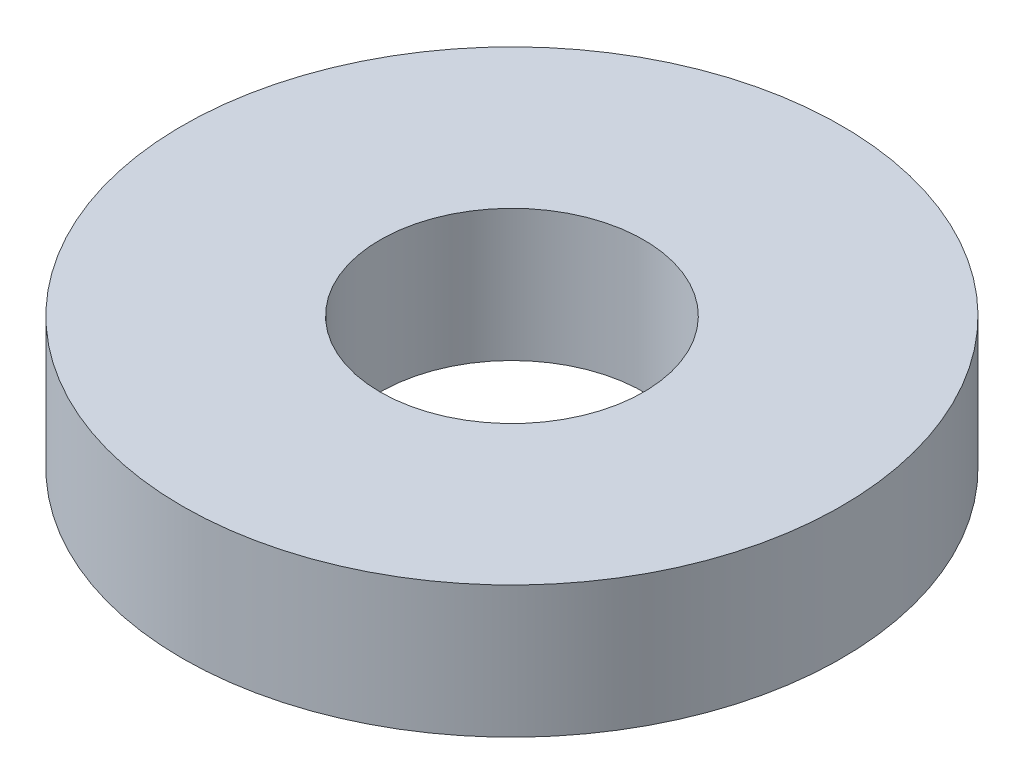
SolidWorks part; units mm, degrees
ref_plane "Front Plane" through (0, 0, 0) normal (0, 0, 1) x (1, 0, 0)
ref_plane "Top Plane" through (0, 0, 0) normal (0, 1, 0) x (1, 0, 0)
ref_plane "Right Plane" through (0, 0, 0) normal (1, 0, 0) x (0, 0, -1)
sketch "Sketch1" plane through (0, 0, 0) normal (0, 1, 0) x (1, 0, 0)
  circle A0 centre (0, 0) radius 25
  circle A1 centre (0, 0) radius 10
  dimension "D1" = 50
  dimension "D2" = 20
extrude "Boss-Extrude1" add sketch "Sketch1" along normal blind 10
